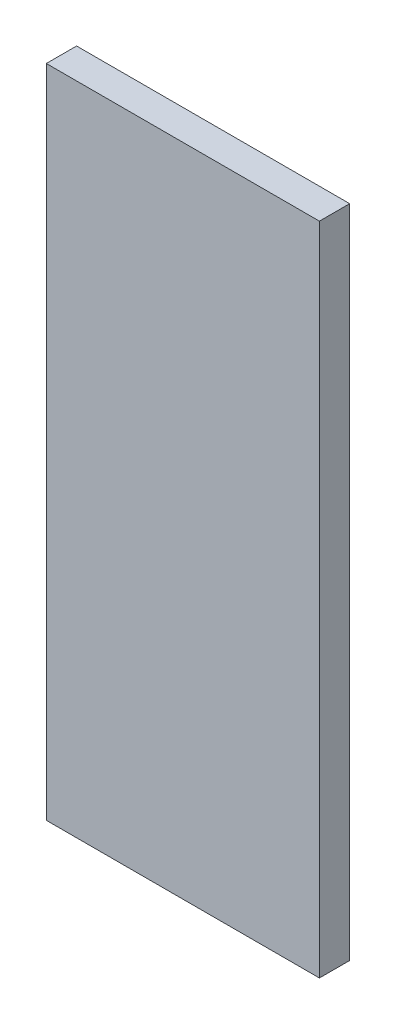
SolidWorks part; units mm, degrees
material "Polyurethane Foam Rigid"
ref_plane "Front Plane" through (0, 0, 0) normal (0, 0, 1) x (1, 0, 0)
ref_plane "Top Plane" through (0, 0, 0) normal (0, 1, 0) x (1, 0, 0)
ref_plane "Right Plane" through (0, 0, 0) normal (1, 0, 0) x (0, 0, -1)
sketch "Sketch1" plane through (0, 0, 0) normal (0, 0, 1) x (1, 0, 0)
  line L1 (-267.5, -825) -> (267.5, -825)
  line L2 (-267.5, -825) -> (-267.5, 825)
  line L3 (-267.5, 825) -> (267.5, 825)
  line L4 (267.5, -825) -> (267.5, 825)
  line L5 (-267.5, -825) -> (267.5, 825) construction
  line L6 (-267.5, 825) -> (267.5, -825) construction
  point P0 (0, 0)
  dimension "D1" = 535
  dimension "D2" = 1650
extrude "Boss-Extrude1" add sketch "Sketch1" along normal blind 76.2
sketch "Sketch2" plane through (267.5, 0, 0) normal (1, 0, 0) x (0, 0, -1)
  line L1 (-76.2, 825) -> (0, 825)
  line L2 (-76.2, 825) -> (-76.2, -825)
  line L3 (-76.2, -825) -> (0, -825)
  line L4 (0, 825) -> (0, -825)
extrude "Boss-Extrude2" add sketch "Sketch2" along normal blind 76.2
sketch "Sketch3" plane through (-267.5, 0, 0) normal (-1, 0, 0) x (0, 0, 1)
  line L1 (0, 825) -> (76.2, 825)
  line L2 (0, 825) -> (0, -825)
  line L3 (0, -825) -> (76.2, -825)
  line L4 (76.2, 825) -> (76.2, -825)
extrude "Boss-Extrude3" add sketch "Sketch3" along normal blind 76.2
